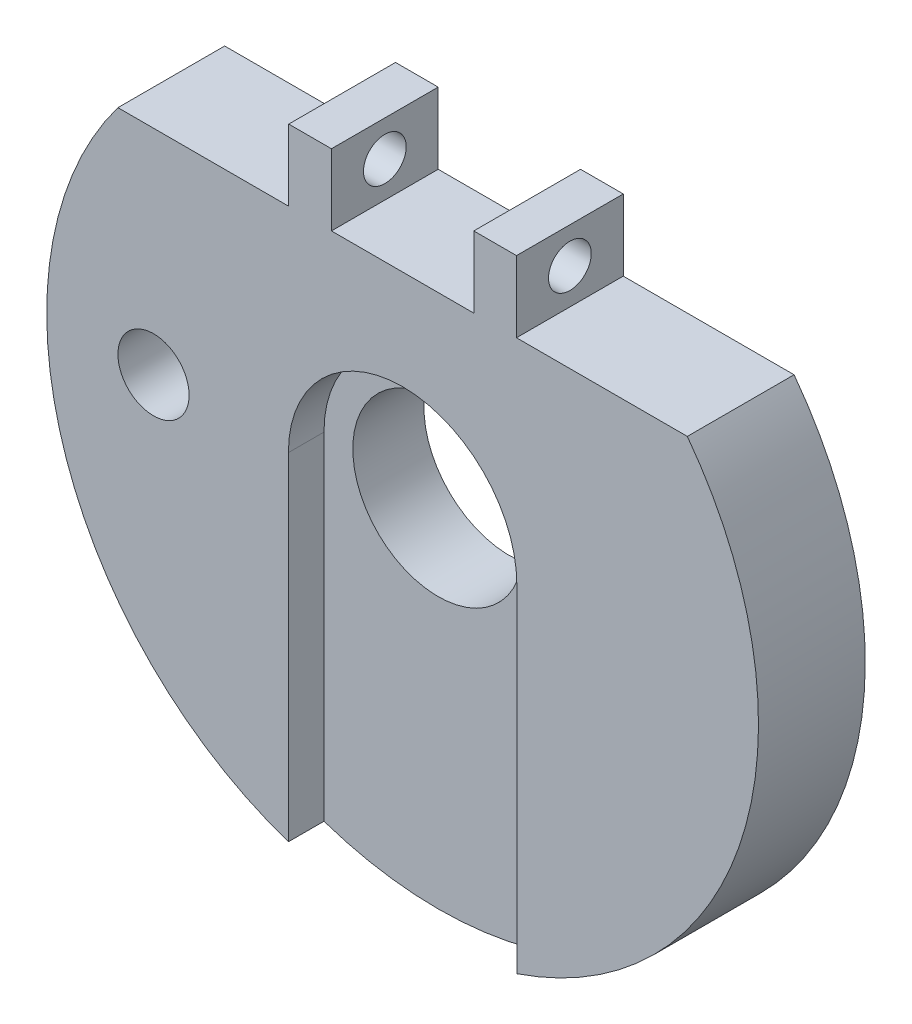
SolidWorks part; units mm, degrees
ref_plane "Piano frontale" through (0, 0, 0) normal (0, 0, 1) x (1, 0, 0)
ref_plane "Piano superiore" through (0, 0, 0) normal (0, 1, 0) x (1, 0, 0)
ref_plane "Piano destro" through (0, 0, 0) normal (1, 0, 0) x (0, 0, -1)
sketch "Schizzo1" plane through (0, 0, 0) normal (0, 0, 1) x (1, 0, 0)
  line L0 (-40, 30) -> (-16, 30)
  line L1 (-16, 30) -> (-16, 40)
  line L2 (-16, 40) -> (-10, 40)
  line L3 (-10, 40) -> (-10, 30)
  line L4 (-10, 30) -> (10, 30)
  line L5 (10, 30) -> (10, 40)
  line L6 (10, 40) -> (16, 40)
  line L7 (16, 40) -> (16, 30)
  line L8 (16, 30) -> (40, 30)
  line L9 (0, 0) -> (0, 68.6185) construction
  arc A0 (-40, 30) -> (40, 30) centre (0, 0) ccw
  point P12 (-16.4207, 56.3359)
  dimension "D1" = 50
  dimension "D2" = 10
  dimension "D3" = 6
  dimension "D4" = 20
  dimension "D5" = 30
extrude "Estrusione-Estrusione1" add sketch "Schizzo1" along normal blind 15
sketch "Schizzo2" plane through (0, 0, 15) normal (0, 0, 1) x (1, 0, 0)
  line L0 (-16.05, 0) -> (-16.05, -50)
  line L1 (16.05, 0) -> (16.05, -50)
  line L2 (16.05, -50) -> (-16.05, -50)
  arc A0 (16.05, 0) -> (-16.05, 0) centre (0, 0) ccw
  arc A1 (-40, 30) -> (40, 30) centre (0, 0) ccw construction
  dimension "D1" = 16.05
extrude "Taglio-Estrusione1" cut sketch "Schizzo2" against normal blind 5
hole_wizard "Foro Ø6.0 (6)-1" positions "Schizzo3" profile "Schizzo4" hole size "Ø6.0" standard "ISO" end condition through all
sketch "Schizzo3" plane through (-16, 0, 0) normal (-1, 0, 0) x (0, 0, 1)
  line L0 (0, 40) -> (15, 30) construction
  point P0 (7.5, 35)
sketch "Schizzo4" plane through (-16, 35, 7.5) normal (0, 1, 0) x (0, 0, 1)
  line L0 (0, 0) -> (0, 66)
  line L1 (0, 66) -> (3, 66)
  line L2 (3, 66) -> (3, 0)
  line L5 (3, 0) -> (0, 0)
  line L11 (0, -6.35) -> (0, 107.95) construction
  dimension "Thru Hole Dia." = 6
  dimension "Thru Hole Depth" = 66
hole_wizard "Foro lamato per Bullone M5 a testa esagonale-1" positions "Schizzo5" profile "Schizzo6" counterbore size "M5" standard "ISO" end condition through all
sketch "Schizzo5" plane through (0, 0, 15) normal (0, 0, 1) x (1, 0, 0)
  line L0 (-35, 0) -> (0, 0) construction
  point P0 (-35, 0)
  dimension "D1" = 35
sketch "Schizzo6" plane through (-35, 0, 15) normal (1, 0, 0) x (0, -1, 0)
  line L0 (0, 0) -> (0, 15)
  line L1 (0, 15) -> (3.5, 15)
  line L3 (3.5, 15) -> (3.5, 10)
  line L4 (3.5, 10) -> (5, 10)
  line L5 (5, 10) -> (5, 0)
  line L7 (5, 0) -> (0, 0)
  line L11 (0, -6.35) -> (0, 107.95) construction
  dimension "Thru Hole Dia." = 7
  dimension "Thru Hole Depth" = 15
  dimension "C'Bore Dia." = 10
  dimension "C'Bore Depth" = 10
hole_wizard "Foro Ø24.0 (24)-1" positions "Schizzo7" profile "Schizzo8" hole size "Ø24.0" standard "ISO" end condition through all
sketch "Schizzo7" plane through (0, 0, 10) normal (0, 0, 1) x (1, 0, 0)
  point P0 (0, 0)
sketch "Schizzo8" plane through (0, 0, 10) normal (1, 0, 0) x (0, -1, 0)
  line L0 (0, 0) -> (0, 10)
  line L1 (0, 10) -> (12, 10)
  line L2 (12, 10) -> (12, 0)
  line L5 (12, 0) -> (0, 0)
  line L11 (0, -6.35) -> (0, 107.95) construction
  dimension "Thru Hole Dia." = 24
  dimension "Thru Hole Depth" = 10
